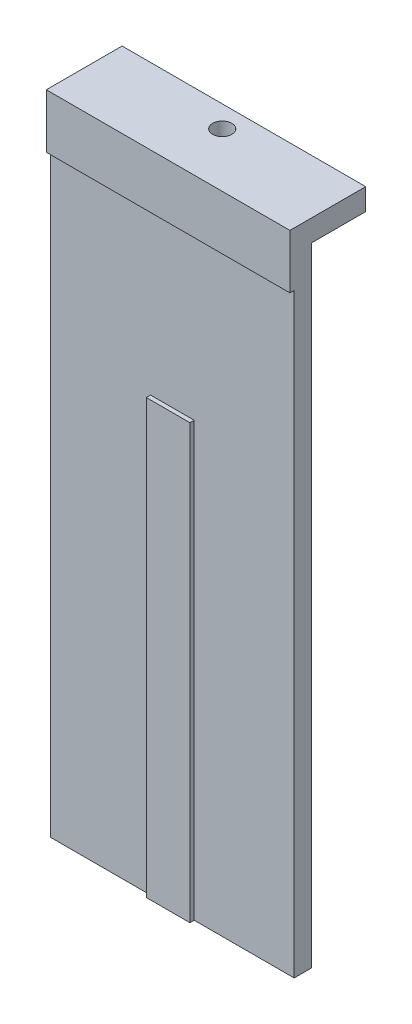
SolidWorks part; units mm, degrees
ref_plane "Front Plane" through (0, 0, 0) normal (0, 0, 1) x (1, 0, 0)
ref_plane "Top Plane" through (0, 0, 0) normal (0, 1, 0) x (1, 0, 0)
ref_plane "Right Plane" through (0, 0, 0) normal (1, 0, 0) x (0, 0, -1)
sketch "Sketch1" plane through (0, 0, 0) normal (0, 1, 0) x (1, 0, 0)
  line L1 (-28.575, -2.54) -> (28.575, -2.54)
  line L2 (-28.575, -2.54) -> (-28.575, 2.54)
  line L3 (-28.575, 2.54) -> (28.575, 2.54)
  line L4 (28.575, -2.54) -> (28.575, 2.54)
  line L5 (-28.575, -2.54) -> (28.575, 2.54) construction
  line L6 (-28.575, 2.54) -> (28.575, -2.54) construction
  point P0 (0, 0)
  dimension "D1" = 57.15
  dimension "D2" = 5.08
extrude "Boss-Extrude1" add sketch "Sketch1" against normal blind 152.4
sketch "Sketch2" plane through (0, 0, 2.54) normal (0, 0, 1) x (1, 0, 0)
  line L0 (-5.125, -152.4) -> (-5.125, -50.8)
  line L1 (-28.575, -152.4) -> (28.575, -152.4) construction
  line L2 (-5.125, -50.8) -> (5.125, -50.8)
  line L3 (5.125, -50.8) -> (5.125, -152.4)
  line L4 (5.125, -152.4) -> (28.575, -152.4)
  line L5 (28.575, -152.4) -> (28.575, -12.7)
  line L6 (28.575, -152.4) -> (28.575, 0) construction
  line L7 (28.575, -12.7) -> (-28.575, -12.7)
  line L8 (-28.575, -152.4) -> (-28.575, 0) construction
  line L9 (-28.575, -12.7) -> (-28.575, -152.4)
  line L10 (-28.575, -152.4) -> (-5.125, -152.4)
  line L11 (0, -152.4) -> (0, 0) construction
  point P19 (5.2694, -101.6)
  point P20 (-12.7306, -101.6)
  point P21 (0, -50.8)
  dimension "D1" = 10.25
  dimension "D2" = 101.6
  dimension "D3" = 139.7
extrude "Cut-Extrude1" cut sketch "Sketch2" against normal blind 1
sketch "Sketch3" plane through (0, 0, -2.54) normal (0, 0, -1) x (-1, 0, 0)
  line L0 (28.575, -152.4) -> (28.575, 0) construction
  line L1 (-28.575, 0) -> (28.575, 0)
  line L2 (-28.575, 0) -> (-28.575, -5.08)
  line L3 (-28.575, -5.08) -> (28.575, -5.08)
  line L4 (28.575, 0) -> (28.575, -5.08)
  dimension "D1" = 5.08
extrude "Boss-Extrude2" add sketch "Sketch3" along normal blind 12.7
sketch "Sketch4" plane through (0, 0, 0) normal (0, 1, 0) x (1, 0, 0)
  line L0 (0, 15.24) -> (0, -2.54) construction
  line L1 (-28.575, 15.24) -> (28.575, 15.24) construction
  line L2 (-28.575, -2.54) -> (28.575, -2.54) construction
  circle A0 centre (0, 10.16) radius 2.25
  dimension "D1" = 4.5
  dimension "D2" = 5.08
extrude "Cut-Extrude2" cut sketch "Sketch4" against normal blind 12.7
